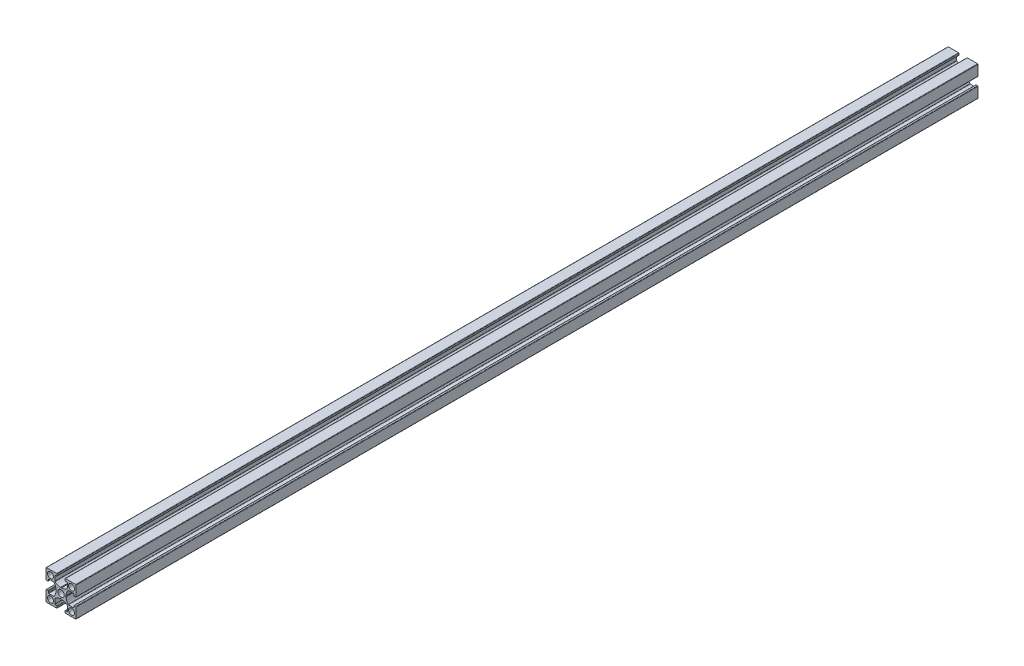
SolidWorks part; units mm, degrees
ref_plane "정면" through (0, 0, 0) normal (0, 0, 1) x (1, 0, 0)
ref_plane "윗면" through (0, 0, 0) normal (0, 1, 0) x (1, 0, 0)
ref_plane "우측면" through (0, 0, 0) normal (1, 0, 0) x (0, 0, -1)
sketch "Model" plane through (0, 0, 0) normal (0, 0, 1) x (1, 0, 0)
  line L0 (2292.4151, 1187.1915) -> (2314.8128, 1187.1915) construction
  line L1 (2307.7639, 1192.1343) -> (2307.7639, 1195.3915)
  line L2 (2307.4639, 1195.6915) -> (2306.5639, 1195.6915)
  line L3 (2306.2639, 1195.9915) -> (2306.2639, 1196.8915)
  line L4 (2306.5639, 1197.1915) -> (2313.3139, 1197.1915)
  line L5 (2313.6139, 1196.8915) -> (2313.6139, 1190.1415)
  line L6 (2313.3139, 1189.8415) -> (2312.4139, 1189.8415)
  line L7 (2312.1139, 1190.1415) -> (2312.1139, 1191.0415)
  line L8 (2311.8139, 1191.3415) -> (2308.5567, 1191.3415)
  line L9 (2306.9212, 1187.4988) -> (2306.6139, 1187.1915)
  line L10 (2306.6139, 1187.1915) -> (2306.9212, 1186.8843)
  line L11 (2308.5567, 1183.0415) -> (2311.8139, 1183.0415)
  line L12 (2312.1139, 1183.3415) -> (2312.1139, 1184.2415)
  line L13 (2312.4139, 1184.5415) -> (2313.3139, 1184.5415)
  line L14 (2313.6139, 1184.2415) -> (2313.6139, 1177.4915)
  line L15 (2313.3139, 1177.1915) -> (2306.5639, 1177.1915)
  line L16 (2306.2639, 1177.4915) -> (2306.2639, 1178.3915)
  line L17 (2306.5639, 1178.6915) -> (2307.4639, 1178.6915)
  line L18 (2307.7639, 1178.9915) -> (2307.7639, 1182.2488)
  line L19 (2303.9212, 1183.8843) -> (2303.6139, 1184.1915)
  line L20 (2303.6139, 1184.1915) -> (2303.3066, 1183.8843)
  line L21 (2299.4639, 1182.2488) -> (2299.4639, 1178.9915)
  line L22 (2299.7639, 1178.6915) -> (2300.6639, 1178.6915)
  line L23 (2300.9639, 1178.3915) -> (2300.9639, 1177.4915)
  line L24 (2300.6639, 1177.1915) -> (2293.9139, 1177.1915)
  line L25 (2293.6139, 1177.4915) -> (2293.6139, 1184.2415)
  line L26 (2293.9139, 1184.5415) -> (2294.8139, 1184.5415)
  line L27 (2295.1139, 1184.2415) -> (2295.1139, 1183.3415)
  line L28 (2295.4139, 1183.0415) -> (2298.6712, 1183.0415)
  line L29 (2300.3066, 1186.8843) -> (2300.6139, 1187.1915)
  line L30 (2300.6139, 1187.1915) -> (2300.3066, 1187.4988)
  line L31 (2298.6712, 1191.3415) -> (2295.4139, 1191.3415)
  line L32 (2295.1139, 1191.0415) -> (2295.1139, 1190.1415)
  line L33 (2294.8139, 1189.8415) -> (2293.9139, 1189.8415)
  line L34 (2293.6139, 1190.1415) -> (2293.6139, 1196.8915)
  line L35 (2293.9139, 1197.1915) -> (2300.6639, 1197.1915)
  line L36 (2300.9639, 1196.8915) -> (2300.9639, 1195.9915)
  line L37 (2300.6639, 1195.6915) -> (2299.7639, 1195.6915)
  line L38 (2299.4639, 1195.3915) -> (2299.4639, 1192.1343)
  line L39 (2303.3066, 1190.4988) -> (2303.6139, 1190.1915)
  line L40 (2303.6139, 1190.1915) -> (2303.9212, 1190.4988)
  line L41 (2294.1139, 1194.1915) -> (2299.1139, 1194.1915) construction
  line L42 (2296.6139, 1196.6915) -> (2296.6139, 1191.6915) construction
  line L43 (2294.1139, 1180.1915) -> (2299.1139, 1180.1915) construction
  line L44 (2296.6139, 1177.6915) -> (2296.6139, 1182.6915) construction
  line L45 (2303.6139, 1198.3904) -> (2303.6139, 1175.9927) construction
  line L46 (2313.1139, 1194.1915) -> (2308.1139, 1194.1915) construction
  line L47 (2310.6139, 1196.6915) -> (2310.6139, 1191.6915) construction
  line L48 (2310.6139, 1177.6915) -> (2310.6139, 1182.6915) construction
  line L49 (2313.1139, 1180.1915) -> (2308.1139, 1180.1915) construction
  circle A0 centre (2303.6139, 1187.1915) radius 2.15
  circle A1 centre (2296.6139, 1194.1915) radius 2
  circle A2 centre (2296.6139, 1180.1915) radius 2
  circle A3 centre (2310.6139, 1194.1915) radius 2
  circle A4 centre (2310.6139, 1180.1915) radius 2
  arc A5 (2307.7639, 1195.3915) -> (2307.4639, 1195.6915) centre (2307.4639, 1195.3915) ccw
  arc A6 (2306.2639, 1195.9915) -> (2306.5639, 1195.6915) centre (2306.5639, 1195.9915) ccw
  arc A7 (2306.5639, 1197.1915) -> (2306.2639, 1196.8915) centre (2306.5639, 1196.8915) ccw
  arc A8 (2313.6139, 1196.8915) -> (2313.3139, 1197.1915) centre (2313.3139, 1196.8915) ccw
  arc A9 (2313.3139, 1189.8415) -> (2313.6139, 1190.1415) centre (2313.3139, 1190.1415) ccw
  arc A10 (2312.1139, 1190.1415) -> (2312.4139, 1189.8415) centre (2312.4139, 1190.1415) ccw
  arc A11 (2312.1139, 1191.0415) -> (2311.8139, 1191.3415) centre (2311.8139, 1191.0415) ccw
  arc A12 (2308.5567, 1191.3415) -> (2308.3217, 1191.2281) centre (2308.5567, 1191.0415) ccw
  arc A13 (2308.3217, 1191.2281) -> (2306.9212, 1187.4988) centre (2313.4048, 1187.1915) ccw
  arc A14 (2306.9212, 1186.8843) -> (2308.3217, 1183.155) centre (2313.4048, 1187.1915) ccw
  arc A15 (2308.3217, 1183.155) -> (2308.5567, 1183.0415) centre (2308.5567, 1183.3415) ccw
  arc A16 (2311.8139, 1183.0415) -> (2312.1139, 1183.3415) centre (2311.8139, 1183.3415) ccw
  arc A17 (2312.4139, 1184.5415) -> (2312.1139, 1184.2415) centre (2312.4139, 1184.2415) ccw
  arc A18 (2313.6139, 1184.2415) -> (2313.3139, 1184.5415) centre (2313.3139, 1184.2415) ccw
  arc A19 (2313.3139, 1177.1915) -> (2313.6139, 1177.4915) centre (2313.3139, 1177.4915) ccw
  arc A20 (2306.2639, 1177.4915) -> (2306.5639, 1177.1915) centre (2306.5639, 1177.4915) ccw
  arc A21 (2306.5639, 1178.6915) -> (2306.2639, 1178.3915) centre (2306.5639, 1178.3915) ccw
  arc A22 (2307.4639, 1178.6915) -> (2307.7639, 1178.9915) centre (2307.4639, 1178.9915) ccw
  arc A23 (2307.7639, 1182.2488) -> (2307.6505, 1182.4837) centre (2307.4639, 1182.2488) ccw
  arc A24 (2307.6505, 1182.4837) -> (2303.9212, 1183.8843) centre (2303.6139, 1177.4007) ccw
  arc A25 (2303.3066, 1183.8843) -> (2299.5774, 1182.4837) centre (2303.6139, 1177.4007) ccw
  arc A26 (2299.5774, 1182.4837) -> (2299.4639, 1182.2488) centre (2299.7639, 1182.2488) ccw
  arc A27 (2299.4639, 1178.9915) -> (2299.7639, 1178.6915) centre (2299.7639, 1178.9915) ccw
  arc A28 (2300.9639, 1178.3915) -> (2300.6639, 1178.6915) centre (2300.6639, 1178.3915) ccw
  arc A29 (2300.6639, 1177.1915) -> (2300.9639, 1177.4915) centre (2300.6639, 1177.4915) ccw
  arc A30 (2293.6139, 1177.4915) -> (2293.9139, 1177.1915) centre (2293.9139, 1177.4915) ccw
  arc A31 (2293.9139, 1184.5415) -> (2293.6139, 1184.2415) centre (2293.9139, 1184.2415) ccw
  arc A32 (2295.1139, 1184.2415) -> (2294.8139, 1184.5415) centre (2294.8139, 1184.2415) ccw
  arc A33 (2295.1139, 1183.3415) -> (2295.4139, 1183.0415) centre (2295.4139, 1183.3415) ccw
  arc A34 (2298.6712, 1183.0415) -> (2298.9061, 1183.155) centre (2298.6712, 1183.3415) ccw
  arc A35 (2298.9061, 1183.155) -> (2300.3066, 1186.8843) centre (2293.8231, 1187.1915) ccw
  arc A36 (2300.3066, 1187.4988) -> (2298.9061, 1191.2281) centre (2293.8231, 1187.1915) ccw
  arc A37 (2298.9061, 1191.2281) -> (2298.6712, 1191.3415) centre (2298.6712, 1191.0415) ccw
  arc A38 (2295.4139, 1191.3415) -> (2295.1139, 1191.0415) centre (2295.4139, 1191.0415) ccw
  arc A39 (2294.8139, 1189.8415) -> (2295.1139, 1190.1415) centre (2294.8139, 1190.1415) ccw
  arc A40 (2293.6139, 1190.1415) -> (2293.9139, 1189.8415) centre (2293.9139, 1190.1415) ccw
  arc A41 (2293.9139, 1197.1915) -> (2293.6139, 1196.8915) centre (2293.9139, 1196.8915) ccw
  arc A42 (2300.9639, 1196.8915) -> (2300.6639, 1197.1915) centre (2300.6639, 1196.8915) ccw
  arc A43 (2300.6639, 1195.6915) -> (2300.9639, 1195.9915) centre (2300.6639, 1195.9915) ccw
  arc A44 (2299.7639, 1195.6915) -> (2299.4639, 1195.3915) centre (2299.7639, 1195.3915) ccw
  arc A45 (2299.4639, 1192.1343) -> (2299.5774, 1191.8994) centre (2299.7639, 1192.1343) ccw
  arc A46 (2299.5774, 1191.8994) -> (2303.3066, 1190.4988) centre (2303.6139, 1196.9824) ccw
  arc A47 (2303.9212, 1190.4988) -> (2307.6505, 1191.8994) centre (2303.6139, 1196.9824) ccw
  arc A48 (2307.6505, 1191.8994) -> (2307.7639, 1192.1343) centre (2307.4639, 1192.1343) ccw
extrude "보스-돌출1" add sketch "Model" along normal blind 600
